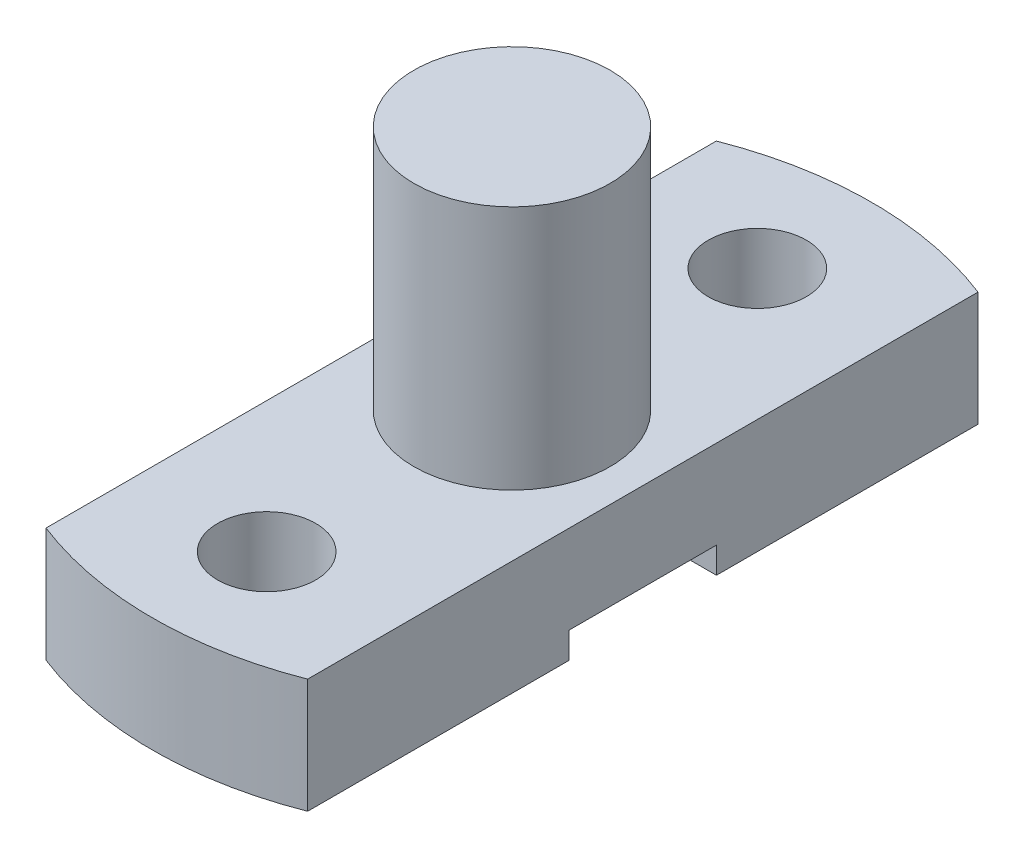
SolidWorks part; units mm, degrees
ref_plane "Front Plane" through (0, 0, 0) normal (0, 0, 1) x (1, 0, 0)
ref_plane "Top Plane" through (0, 0, 0) normal (0, 1, 0) x (1, 0, 0)
ref_plane "Right Plane" through (0, 0, 0) normal (1, 0, 0) x (0, 0, -1)
sketch "Sketch1" plane through (0, 0, 0) normal (0, 1, 0) x (1, 0, 0)
  line L0 (-192.4315, 0) -> (188.2614, 0) construction
  line L1 (0, 98.6392) -> (0, -114.2672) construction
  line L2 (-40, 102.4695) -> (-40, -102.4695)
  line L3 (40, 102.4695) -> (40, -102.4695)
  arc A0 (-40, -102.4695) -> (40, -102.4695) centre (0, 0) ccw
  arc A1 (40, 102.4695) -> (-40, 102.4695) centre (0, 0) ccw
  circle A2 centre (0, 75) radius 15
  circle A3 centre (0, -75) radius 15
  dimension "D1" = 220
  dimension "D7" = 30
  dimension "D8" = 30
  dimension "D2" = 40
  dimension "D3" = 40
  dimension "D4" = 150
  dimension "D5" = 75
  dimension "D6" = 75
extrude "Boss-Extrude1" add sketch "Sketch1" along normal blind 35
sketch "Sketch2" plane through (0, 35, 0) normal (0, 1, 0) x (1, 0, 0)
  circle A0 centre (0, 0) radius 30
  dimension "D1" = 60
extrude "Boss-Extrude2" add sketch "Sketch2" along normal blind 75
sketch "Sketch4" plane through (40, 0, 0) normal (1, 0, 0) x (0, 0, -1)
  line L0 (-102.4695, 0) -> (102.4695, 0) construction
  line L1 (22.5, 0) -> (-22.5, 0)
  line L2 (22.5, 0) -> (22.5, 8)
  line L3 (22.5, 8) -> (-22.5, 8)
  line L4 (-22.5, 0) -> (-22.5, 8)
  line L5 (0, 0) -> (0, 74.9208) construction
  point P8 (22.5, 4)
  point P10 (-22.5, 4)
  dimension "D1" = 45
  dimension "D2" = 8
  dimension "D3" = 22.5
extrude "Cut-Extrude1" cut sketch "Sketch4" against normal through all
